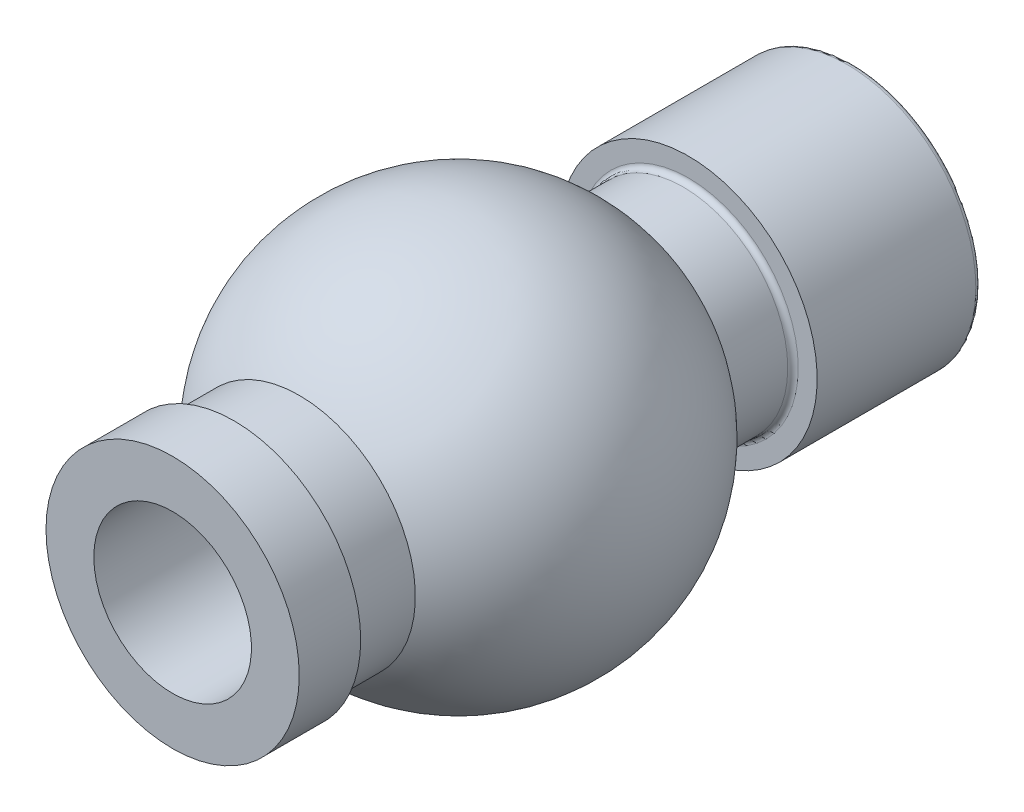
SolidWorks part; units mm, degrees
ref_plane "Front Plane" through (0, 0, 0) normal (0, 0, 1) x (1, 0, 0)
ref_plane "Top Plane" through (0, 0, 0) normal (0, 1, 0) x (1, 0, 0)
ref_plane "Right Plane" through (0, 0, 0) normal (1, 0, 0) x (0, 0, -1)
sketch "Sketch1" plane through (0, 0, 0) normal (0, 0, 1) x (1, 0, 0)
  circle A0 centre (0, 0) radius 2.45
  circle A1 centre (0, 0) radius 1.5
  dimension "D1" = 4.9
  dimension "D2" = 3
extrude "Boss-Extrude1" add sketch "Sketch1" along normal blind 3.12
sketch "Sketch2" plane through (0, 0, 3.12) normal (0, 0, 1) x (1, 0, 0)
  circle A0 centre (0, 0) radius 1.5
  circle A1 centre (0, 0) radius 1.99
  circle A2 centre (0, 0) radius 1.5
  circle M4 centre (0, 0) radius 1.5
  dimension "D1" = 3.98
extrude "Boss-Extrude2" add sketch "Sketch2" along normal blind 1.2 contours A1 M4
fillet "Fillet1" radius 0.1 2 edges at (2.45, 0, 0) (1.99, 0, 3.12)
sketch "Sketch3" plane through (0, 0, 0) normal (1, 0, 0) x (0, 0, -1)
  line L0 (-4.32, 0) -> (-8.2383, 0) construction
  line L1 (-4.32, 1.99) -> (-4.32, -1.99) construction
  line L2 (-4.32, 0) -> (-4.32, 1.99)
  line L4 (-3.22, 1.99) -> (-4.32, 1.99) construction
  line L5 (-8.2383, 0) -> (-10.528, 0) construction
  line L6 (-10.528, 0) -> (-4.32, 0)
  line L7 (-10.528, 2.21) -> (-10.528, 0)
  arc A0 (-4.32, 1.99) -> (-10.528, 2.21) centre (-7.4984, 0) ccw
  dimension "D1" = 7.5
  dimension "D2" = 2.21
sketch "Sketch4" plane through (0, 0, 0) normal (1, 0, 0) x (0, 0, -1)
  line L0 (-4.32, 0) -> (-13.6532, 0) construction
revolve "Revolve1" add sketch "Sketch3" angle 360 about L0
sketch "Sketch5" plane through (0, 0, 10.528) normal (0, 0, 1) x (1, 0, 0)
  circle A0 centre (0, 0) radius 1.5
  dimension "D1" = 3
extrude "Cut-Extrude1" cut sketch "Sketch5" against normal blind 8.2
sketch "Sketch6" plane through (0, 0, 10.528) normal (0, 0, 1) x (1, 0, 0)
  circle A0 centre (0, 0) radius 1.5
  circle A2 centre (0, 0) radius 2.21
extrude "Boss-Extrude3" add sketch "Sketch6" along normal blind 1.24
sketch "Sketch7" plane through (0, 0, 11.768) normal (0, 0, 1) x (1, 0, 0)
  circle A0 centre (0, 0) radius 2.41
  circle A1 centre (0, 0) radius 1.5
  dimension "D1" = 4.82
extrude "Boss-Extrude4" add sketch "Sketch7" along normal blind 1.17
ref_plane "Plane1" through (0, 0, 7.425) normal (0, 0, -1) x (-1, 0, 0)
sketch "Sketch8" plane through (0, 0, 7.425) normal (0, 0, -1) x (-1, 0, 0)
  point P0 (0, 0)
  point P3 (0, 0)
